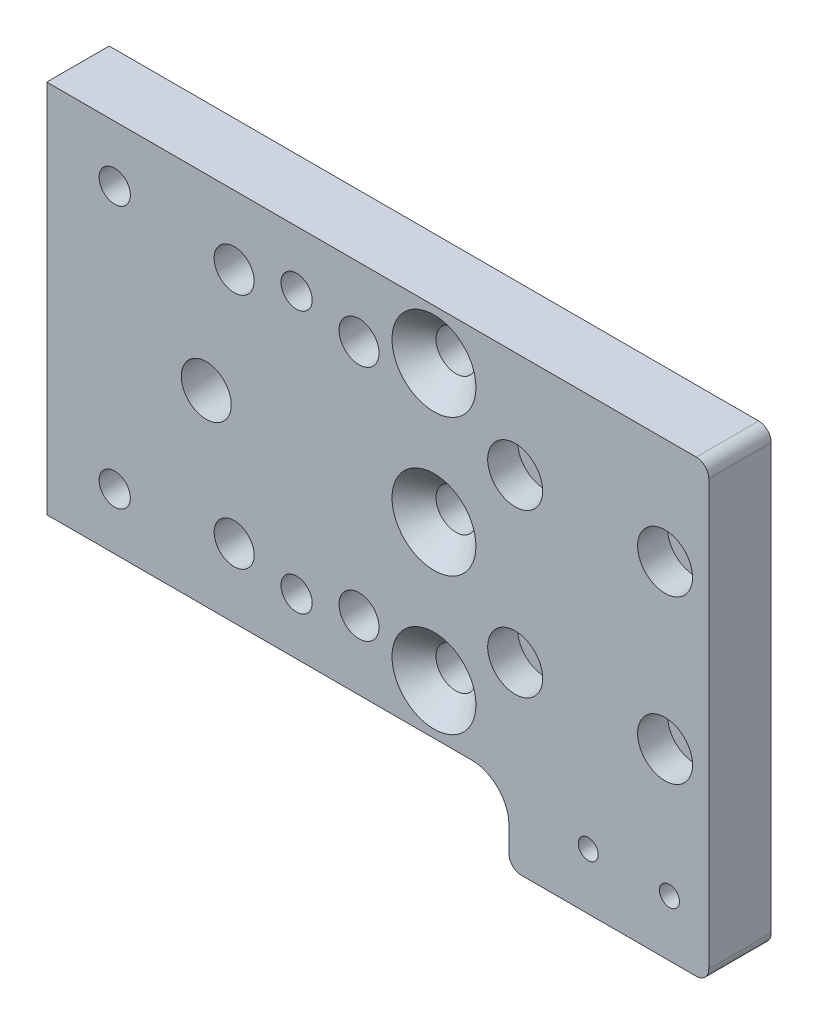
SolidWorks part; units mm, degrees
ref_plane "Piano frontale" through (0, 0, 0) normal (0, 0, 1) x (1, 0, 0)
ref_plane "Piano superiore" through (0, 0, 0) normal (0, 1, 0) x (1, 0, 0)
ref_plane "Piano destro" through (0, 0, 0) normal (1, 0, 0) x (0, 0, -1)
sketch "Schizzo1" plane through (0, 0, 0) normal (0, 0, 1) x (1, 0, 0)
  line L1 (-26, -15) -> (26, -15)
  line L2 (-26, -15) -> (-26, 15)
  line L3 (-26, 15) -> (26, 15)
  line L4 (26, -15) -> (26, 15)
  line L5 (-26, -15) -> (26, 15) construction
  line L6 (-26, 15) -> (26, -15) construction
  point P0 (0, 0)
  dimension "D1" = 52
  dimension "D2" = 30
extrude "Estrusione-Estrusione1" add sketch "Schizzo1" along normal blind 5
hole_wizard "Foro lamato per Vite M2 a testa cilindrica-1" positions "Schizzo3D1" profile "Schizzo2" counterbore size "M2" standard "ISO"
sketch3d "Schizzo3D1"
  line L0 (26, -15, 5) -> (26, 15, 5) construction
  line L5 (26, 0, 5) -> (8.8759, 0, 5) construction
  point P0 (11.5, 6.5, 5)
  point P2 (23.5, 6.5, 5)
  point P4 (11.5, -6.5, 5)
  point P6 (23.5, -6.5, 5)
  dimension "D4" = 6.5
  dimension "D1" = 12
  dimension "D2" = 13
  dimension "D3" = 2.5
sketch "Schizzo2" plane through (11.5, 6.5, 5) normal (1, 0, 0) x (0, -1, 0)
  line L0 (0, 0) -> (0, 9.1609)
  line L1 (0, 9.1609) -> (1.1, 8.5)
  line L2 (1.1, 8.5) -> (1.1, 2.4)
  line L3 (1.1, 2.4) -> (2.2, 2.4)
  line L4 (2.2, 2.4) -> (2.2, 0)
  line L5 (2.2, 0) -> (0, 0)
  line L10 (0, 9.1609) -> (-1.1, 8.5) construction
  line L11 (0, -6.35) -> (0, 107.95) construction
  dimension "Hole Dia." = 2.2
  dimension "Hole Depth" = 8.5
  dimension "C'Bore Dia." = 4.4
  dimension "C'Bore Depth" = 2.4
  dimension "Drill Angle" = 118
hole_wizard "Foro svasato per Vite M3-1" positions "Schizzo5" profile "Schizzo6" countersink size "M3" standard "ISO"
sketch "Schizzo5" plane through (0, 0, 0) normal (0, 0, -1) x (-1, 0, 0)
  line L0 (26, 15) -> (26, -15) construction
  line L1 (26, 0) -> (4.1558, 0) construction
  point P0 (11, -9.5)
  point P2 (1, -9.5)
  point P4 (11, 9.5)
  point P6 (1, 9.5)
  dimension "D1" = 19
  dimension "D2" = 10
  dimension "D3" = 15
  dimension "D4" = 9.5
sketch "Schizzo6" plane through (-11, -9.5, 0) normal (1, 0, 0) x (0, 1, 0)
  line L0 (0, 0) -> (0, 9.4614)
  line L1 (0, 9.4614) -> (1.6, 8.5)
  line L2 (1.6, 8.5) -> (1.6, 1.76)
  line L3 (1.6, 1.76) -> (3.36, 0)
  line L5 (3.36, 0) -> (0, 0)
  line L6 (-1.6, 1.76) -> (-3.36, 0) construction
  line L10 (0, 9.4614) -> (-1.6, 8.5) construction
  line L11 (0, -6.35) -> (0, 107.95) construction
  dimension "Hole Dia." = 3.2
  dimension "Hole Depth" = 8.5
  dimension "Near C'Sink Dia." = 6.72
  dimension "Near C'Sink Angle" = 90
  dimension "Drill Angle" = 118
hole_wizard "Foro Ø4.0 (4)-1" positions "Schizzo3D2" profile "Schizzo7" hole size "Ø4.0" standard "ISO"
sketch3d "Schizzo3D2"
  line L0 (-26, 0, 5) -> (-6.5542, 0, 5) construction
  line L1 (-26, 15, 5) -> (-26, -15, 5) construction
  line L3 (-11, 9.5, 5) -> (-11, -9.5, 5) construction
  line L4 (-11, 9.5, 5) -> (-11, 9.5, 1.76) construction
  line L5 (-11, -9.5, 5) -> (-11, -9.5, 1.76) construction
  point P0 (-13.23, 0, 5)
  dimension "D1" = 2.23
sketch "Schizzo7" plane through (-13.23, 0, 5) normal (1, 0, 0) x (0, -1, 0)
  line L0 (0, 0) -> (0, 9.7017)
  line L1 (0, 9.7017) -> (2, 8.5)
  line L2 (2, 8.5) -> (2, 0)
  line L5 (2, 0) -> (0, 0)
  line L10 (0, 9.7017) -> (-2, 8.5) construction
  line L11 (0, -6.35) -> (0, 107.95) construction
  dimension "Hole Dia." = 4
  dimension "Hole Depth" = 8.5
  dimension "Drill Angle" = 118
hole_wizard "Foro filettato M3-1" positions "Schizzo3D3" profile "Schizzo8" tap size "M3" standard "ISO"
sketch3d "Schizzo3D3"
  line L0 (-26, 0, 5) -> (-4.6175, 0, 5) construction
  line L1 (-26, 15, 5) -> (-26, -15, 5) construction
  line L3 (-11, 9.5, 5) -> (-11, 18.1388, 5) construction
  line L4 (-11, 9.5, 5) -> (-11, 9.5, 1.76) construction
  point P0 (-20.56, 10.5, 5)
  point P2 (-6, 10.5, 5)
  point P4 (-6, -10.5, 5)
  point P6 (-20.56, -10.5, 5)
  dimension "D3" = 10.5
  dimension "D1" = 21
  dimension "D2" = 14.56
  dimension "D4" = 5
sketch "Schizzo8" plane through (-20.56, 10.5, 5) normal (1, 0, 0) x (0, -1, 0)
  line L0 (0, 0) -> (0, 9.2511)
  line L1 (0, 9.2511) -> (1.25, 8.5)
  line L2 (1.25, 8.5) -> (1.25, 0)
  line L5 (1.25, 0) -> (0, 0)
  line L10 (0, 9.2511) -> (-1.25, 8.5) construction
  line L11 (0, -6.35) -> (0, 107.95) construction
  dimension "Tap Drill Dia." = 2.5
  dimension "Tap Drill Depth" = 8.5
  dimension "Drill Angle" = 118
cosmetic thread "Filettatura del foro1" parameters "D1"=6, "D2"=3
cosmetic thread "Filettatura del foro2" parameters "D1"=6, "D2"=3
cosmetic thread "Filettatura del foro3" parameters "D1"=6, "D2"=3
cosmetic thread "Filettatura del foro4" parameters "D1"=6, "D2"=3
sketch "Schizzo9" plane through (0, 0, 5) normal (0, 0, 1) x (1, 0, 0)
  line L0 (26, -15) -> (26, 15) construction
  point P0 (5, 11)
  point P1 (5, 0)
  point P2 (5, -11)
  dimension "D1" = 21
  dimension "D2" = 11
  dimension "D3" = 11
hole_wizard "Foro svasato per Vite M3-2" positions "Schizzo3D4" profile "Schizzo10" countersink size "M3" standard "ISO" end condition through all
sketch3d "Schizzo3D4"
  point P0 (5, 11, 5)
  point P3 (5, 0, 5)
  point P6 (5, -11, 5)
sketch "Schizzo10" plane through (5, 11, 5) normal (1, 0, 0) x (0, -1, 0)
  line L0 (0, 0) -> (0, 5)
  line L1 (0, 5) -> (1.6, 5)
  line L2 (1.6, 5) -> (1.6, 1.76)
  line L3 (1.6, 1.76) -> (3.36, 0)
  line L5 (3.36, 0) -> (0, 0)
  line L6 (-1.6, 1.76) -> (-3.36, 0) construction
  line L11 (0, -6.35) -> (0, 107.95) construction
  dimension "Thru Hole Dia." = 3.2
  dimension "Thru Hole Depth" = 5
  dimension "Near C'Sink Dia." = 6.72
  dimension "Near C'Sink Angle" = 90
sketch "Schizzo11" plane through (0, -15, 0) normal (0, -1, 0) x (1, 0, 0)
  line L0 (-26, 0) -> (26, 0) construction
  line L1 (26, 5) -> (11, 5)
  line L2 (26, 5) -> (26, 0)
  line L3 (26, 0) -> (11, 0)
  line L4 (11, 5) -> (11, 0)
  dimension "D1" = 15
extrude "Estrusione-Estrusione2" add sketch "Schizzo11" along normal blind 6
sketch "Schizzo12" plane through (0, 0, 5) normal (0, 0, 1) x (1, 0, 0)
  line L0 (26, -21) -> (26, 15) construction
  circle A0 centre (23.5, -6.5) radius 1.1 construction
  point P0 (23.85, -16.5)
  point P1 (17.35, -16.5)
  dimension "D1" = 6.5
  dimension "D2" = 10
  dimension "D3" = 2.15
hole_wizard "Foro filettato M2-1" positions "Schizzo3D5" profile "Schizzo13" tap size "M2" standard "ISO"
sketch3d "Schizzo3D5"
  point P0 (17.35, -16.5, 5)
  point P3 (23.85, -16.5, 5)
sketch "Schizzo13" plane through (17.35, -16.5, 5) normal (1, 0, 0) x (0, -1, 0)
  line L0 (0, 0) -> (0, 6.4807)
  line L1 (0, 6.4807) -> (0.8, 6)
  line L2 (0.8, 6) -> (0.8, 0)
  line L5 (0.8, 0) -> (0, 0)
  line L10 (0, 6.4807) -> (-0.8, 6) construction
  line L11 (0, -6.35) -> (0, 107.95) construction
  dimension "Tap Drill Dia." = 1.6
  dimension "Tap Drill Depth" = 6
  dimension "Drill Angle" = 118
cosmetic thread "Filettatura del foro5" parameters "D1"=4, "D2"=2
cosmetic thread "Filettatura del foro6" parameters "D1"=4, "D2"=2
sketch "Schizzo14" plane through (0, -21, 0) normal (0, -1, 0) x (1, 0, 0)
  line L1 (26, 5) -> (27, 5)
  line L2 (26, 5) -> (26, 0)
  line L3 (26, 0) -> (27, 0)
  line L4 (27, 5) -> (27, 0)
  dimension "D1" = 1
extrude "Estrusione-Estrusione3" add sketch "Schizzo14" against normal up to surface (36 mm away) up to face at (0, 15, 2.5)
fillet "Raccordo1" radius 1 3 edges at (27, 15, 2.5) (27, -21, 2.5) (11, -21, 2.5)
fillet "Raccordo2" radius 3 1 edges at (11, -15, 2.5)
equation "\"D4@Schizzo3D1\"=\"D2@Schizzo3D1\"/2"
equation "\"D4@Schizzo5\"=\"D1@Schizzo5\"/2"
equation "\"D3@Schizzo3D3\"=\"D1@Schizzo3D3\"/2"
